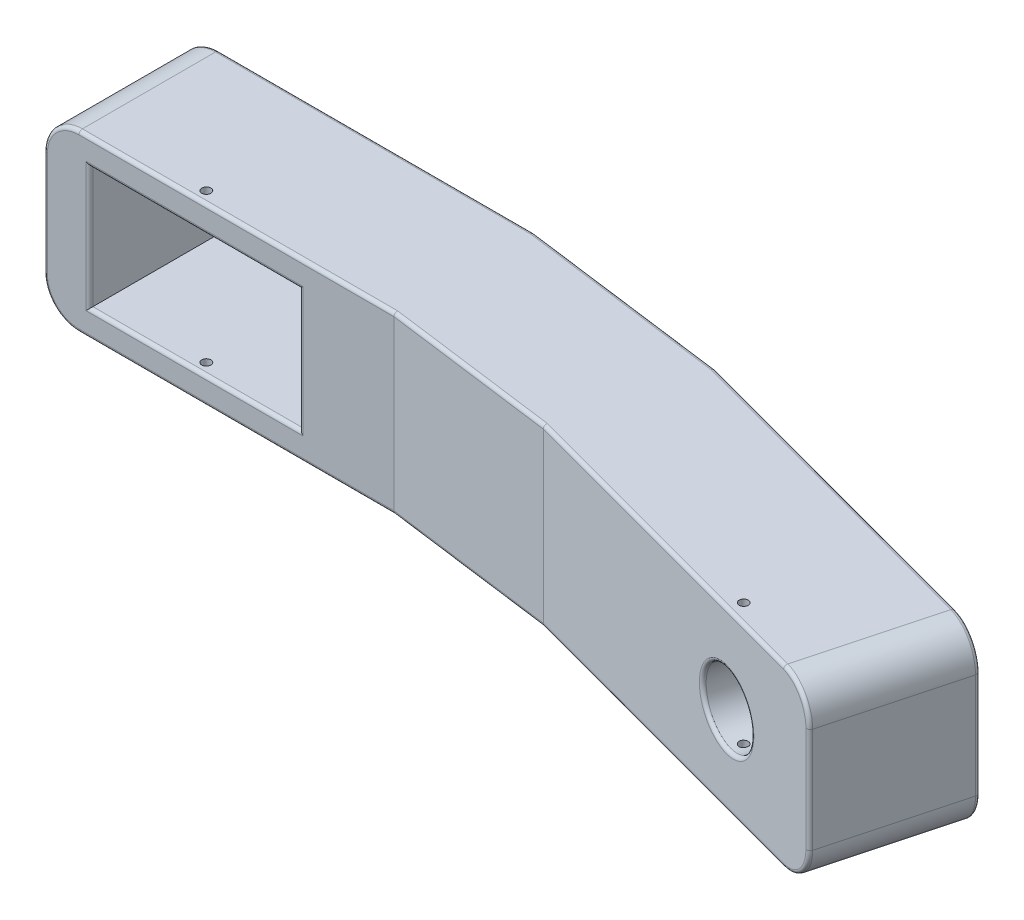
SolidWorks part; units mm, degrees
ref_plane "前基準面" through (0, 0, 0) normal (0, 0, 1) x (1, 0, 0)
ref_plane "上基準面" through (0, 0, 0) normal (0, 1, 0) x (1, 0, 0)
ref_plane "右基準面" through (0, 0, 0) normal (1, 0, 0) x (0, 0, -1)
sketch "草圖1" plane through (0, 0, 0) normal (0, 0, 1) x (1, 0, 0)
  line L1 (0, 0) -> (100, 0)
  line L2 (0, 0) -> (0, 50)
  line L3 (0, 50) -> (100, 50)
  line L4 (100, 0) -> (100, 50)
  dimension "D1" = 100
  dimension "D2" = 50
extrude "填料-伸長1" add sketch "草圖1" along normal blind 40
sketch "草圖2" plane through (0, 0, 40) normal (0, 0, 1) x (1, 0, 0)
  line L3 (0, 25) -> (100, 25) construction
  line L4 (13, 42.5) -> (73, 42.5)
  line L5 (13, 42.5) -> (13, 7.5)
  line L6 (13, 7.5) -> (73, 7.5)
  line L7 (73, 42.5) -> (73, 7.5)
  line L8 (0, 50) -> (0, 0) construction
  line L9 (100, 0) -> (100, 50) construction
  point P16 (73, 25)
  dimension "D1" = 60
  dimension "D2" = 35
  dimension "D3" = 13
extrude "除料-伸長1" cut sketch "草圖2" against normal blind 70 contours L5 L3 L7 L4 | L3 L5 L6 L7
sketch "草圖4" plane through (0, 50, 0) normal (0, 1, 0) x (1, 0, 0)
  line L0 (13, -20) -> (73, -20) construction
  line L1 (13, 0) -> (13, -40) construction
  line L2 (73, 0) -> (73, -40) construction
  line L3 (43, -20) -> (43, -40)
  line L4 (100, -40) -> (0, -40) construction
  circle A0 centre (43, -36.6) radius 1.3
  dimension "D1" = 2.6
  dimension "D2" = 3.4
extrude "除料-伸長2" cut sketch "草圖4" against normal through all contours A0
sketch "草圖5" plane through (0, 50, 0) normal (0, 1, 0) x (1, 0, 0)
  line L0 (100, 0) -> (159.4867, -7.8316)
  line L1 (159.4867, -7.8316) -> (262.937, -35.551)
  line L2 (262.937, -35.551) -> (252.5842, -74.188)
  line L3 (252.5842, -74.188) -> (149.1339, -46.4686)
  line L4 (149.1339, -46.4686) -> (100, -40)
  line L5 (124.567, -43.2343) -> (137.8642, 57.7686) construction
  line L6 (100, -40) -> (100, 0) construction
  line L7 (159.4867, -7.8316) -> (149.1339, -46.4686) construction
  line L8 (50, 0) -> (50, -40) construction
  line L11 (100, 0) -> (0, 0) construction
  line L12 (100, -40) -> (0, -40) construction
  line L13 (200.8591, -60.3283) -> (211.2119, -21.6913) construction
  line L18 (100, 0) -> (0, 0)
  line L19 (0, 0) -> (0, -40)
  line L20 (0, -40) -> (100, -40)
  line L21 (100, -40) -> (100, 0)
  line L22 (100, 0) -> (0, 0)
  line L23 (0, 0) -> (0, -40)
  line L24 (0, -40) -> (100, -40)
  line M19 (100, -40) -> (100, 0)
  dimension "D1" = 30
  dimension "D2" = 30
  dimension "D3" = 82.5
  dimension "D4" = 15
  dimension "D5" = 0
extrude "填料-伸長2" add sketch "草圖5" against normal up to surface (50 mm away) contours L4 L3 L2 L1 L0 M19 up to face at (43, 0, 37.9)
sketch "草圖6" plane through (-1.6271, 0, 6.0723) normal (-0.2588, 0, 0.9659) x (0.9659, 0, 0.2588)
  line L0 (230.147, 50) -> (230.147, 0) construction
  line L1 (263.1789, 50) -> (156.0793, 50) construction
  line L2 (156.0793, 0) -> (263.1789, 0) construction
  circle A0 centre (230.147, 25) radius 10
  dimension "D1" = 20
extrude "除料-伸長3" cut sketch "草圖6" against normal through all
sketch "草圖7" plane through (0, 50, 0) normal (0, 1, 0) x (1, 0, 0)
  line L0 (235.5135, -48.9084) -> (216.195, -43.732) construction
  line L1 (230.3371, -68.2269) -> (240.6899, -29.5899) construction
  line L2 (221.3714, -24.4135) -> (211.0186, -63.0506) construction
  line L3 (225.8543, -46.3202) -> (220.6779, -65.6387) construction
  line L4 (252.5842, -74.188) -> (149.1339, -46.4686) construction
  circle A0 centre (221.7132, -61.775) radius 1.3
  dimension "D1" = 2.6
  dimension "D2" = 4
extrude "除料-伸長4" cut sketch "草圖7" against normal through all
fillet "圓角1" radius 10 4 edges at (257.7606, 0, 54.8695) (257.7606, 50, 54.8695) (0, 50, 20) (0, 0, 20)
fillet "圓角2" radius 1 33 edges at (55, 0, 0) (2.9289, 2.9289, 0) (0, 25, 0) (2.9289, 47.0711, 0) (206.3822, 0, 20.3972) (260.1079, 2.9289, 34.7929) (262.937, 25, 35.551) (260.1079, 47.0711, 34.7929) (55, 0, 40) (2.9289, 2.9289, 40) (0, 25, 40) (2.9289, 47.0711, 40) (196.0295, 0, 59.0342) (249.7551, 2.9289, 73.43) (252.5842, 25, 74.188) (249.7551, 47.0711, 73.43) (73, 25, 0) (43, 42.5, 0) (13, 25, 0) (43, 7.5, 0) (13, 25, 40) (43, 42.5, 40) (43, 7.5, 40) (73, 25, 40) (230.3371, 25, 68.2269) (129.7433, 0, 3.9158) (129.7433, 50, 3.9158) (55, 50, 0) (206.3822, 50, 20.3972) (124.567, 0, 43.2343) (124.567, 50, 43.2343) (55, 50, 40) (196.0295, 50, 59.0342)
sketch "草圖8" plane through (0, 50, 0) normal (0, 1, 0) x (1, 0, 0)
  line L0 (23.8209, -1) -> (23.8209, -800.3191) construction
  line L1 (99.9345, -1) -> (10, -1) construction
  line L2 (23.8209, -40) -> (227.5478, -40) construction
  line L3 (100, -40) -> (10, -40) construction
  line L4 (221.7132, -61.775) -> (267.3734, 108.6311) construction
  line L5 (221.7132, -61.775) -> (23.8209, -800.3191) construction
  line L6 (0, -39) -> (0, -1) construction
  dimension "D1" = 23.8209
  dimension "D2" = 15
  dimension "D3" = 203.7269
  dimension "D4" = 760.3191
